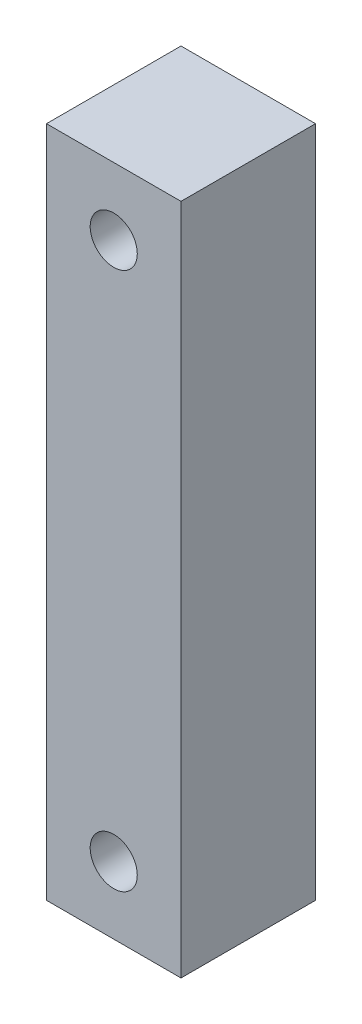
SolidWorks part; units mm, degrees
ref_plane "Front Plane" through (0, 0, 0) normal (0, 0, 1) x (1, 0, 0)
ref_plane "Top Plane" through (0, 0, 0) normal (0, 1, 0) x (1, 0, 0)
ref_plane "Right Plane" through (0, 0, 0) normal (1, 0, 0) x (0, 0, -1)
sketch "Sketch1" plane through (0, 0, 0) normal (0, 1, 0) x (1, 0, 0)
  line L1 (-5, -5) -> (5, -5)
  line L2 (-5, -5) -> (-5, 5)
  line L3 (-5, 5) -> (5, 5)
  line L4 (5, -5) -> (5, 5)
  line L5 (-5, -5) -> (5, 5) construction
  line L6 (-5, 5) -> (5, -5) construction
  point P0 (0, 0)
  dimension "D1" = 5
extrude "Boss-Extrude1" add sketch "Sketch1" along normal blind 50
sketch "Sketch2" plane through (0, 0, 5) normal (0, 0, 1) x (1, 0, 0)
  line L0 (0, 0) -> (0, 5)
  line L2 (-5, 0) -> (5, 0) construction
  circle A0 centre (0, 5) radius 1.75
  circle A1 centre (0, 45) radius 1.75
  dimension "D1" = 3.5
  dimension "D2" = 5
  dimension "D3" = 45
extrude "Cut-Extrude1" cut sketch "Sketch2" against normal blind 14
